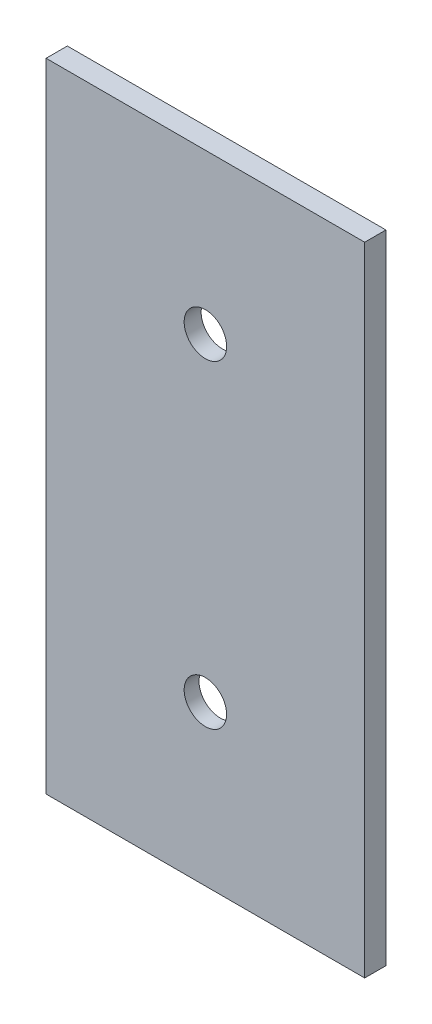
SolidWorks part; units mm, degrees
ref_plane "Front Plane" through (0, 0, 0) normal (0, 0, 1) x (1, 0, 0)
ref_plane "Top Plane" through (0, 0, 0) normal (0, 1, 0) x (1, 0, 0)
ref_plane "Right Plane" through (0, 0, 0) normal (1, 0, 0) x (0, 0, -1)
sketch "Sketch2" plane through (0, 0, 0) normal (0, 0, 1) x (0, -1, 0)
  line L1 (-37.5, 37.5) -> (112.5, 37.5)
  line L2 (-37.5, 37.5) -> (-37.5, -37.5)
  line L3 (-37.5, -37.5) -> (112.5, -37.5)
  line L4 (112.5, 37.5) -> (112.5, -37.5)
  circle A2 centre (0, 0) radius 5
  circle A3 centre (75, 0) radius 5
  point P2 (-37.5, 0)
  point P10 (0, 0)
  dimension "D1" = 0
  dimension "D2" = 37.5
  dimension "D5" = 10
  dimension "D6" = 0
  dimension "D7" = 10
  dimension "D3" = 150
  dimension "D4" = 75
  dimension "D8" = 37.5
extrude "Boss-Extrude1" add sketch "Sketch2" along normal blind 5 contours L2 L3 L4 L1
sketch "Sketch3" plane through (0, 0, 0) normal (0, 0, -1) x (-1, 0, 0)
  circle A0 centre (0, 0) radius 18.75
  dimension "D1" = 37.5
extrude "Cut-Extrude1" cut sketch "Sketch3" against normal blind 1
sketch "Sketch4" plane through (0, 0, 0) normal (0, 0, 1) x (1, 0, 0)
  text T0 "V3.0 - 1mm" font "Century Gothic" height in points 28
  text T1 "V3.0 - 1.5  mm" font "Century Gothic" height in points 28
  point P2 (21.782, -108.1444)
extrude "Cut-Extrude2" cut sketch "Sketch4" along normal blind 1
sketch "Sketch5" plane through (0, 0, 0) normal (0, 0, -1) x (-1, 0, 0)
  circle A0 centre (0, -75) radius 18.75
  dimension "D1" = 37.5
extrude "Cut-Extrude3" cut sketch "Sketch5" against normal blind 1.5
equation "\"NUT\"=1"
